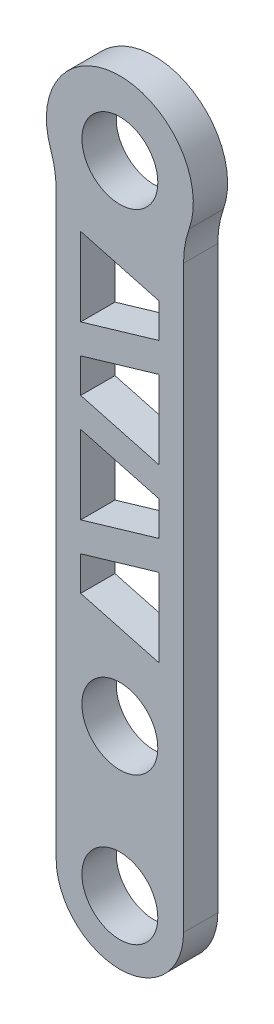
SolidWorks part; units mm, degrees
ref_plane "Front Plane" through (0, 0, 0) normal (0, 0, 1) x (1, 0, 0)
ref_plane "Top Plane" through (0, 0, 0) normal (0, 1, 0) x (1, 0, 0)
ref_plane "Right Plane" through (0, 0, 0) normal (1, 0, 0) x (0, 0, -1)
sketch "Sketch1" plane through (0, 0, 0) normal (0, 0, 1) x (1, 0, 0)
  line L0 (-1.1218, 98.318) -> (-1.1218, -78.4144) construction
  line L1 (-14.1218, 65.8174) -> (-14.1218, -52.5207)
  line L2 (-9.1218, 3.9577) -> (-9.1218, -3.0423)
  line L3 (-9.1218, -3.0423) -> (6.8782, -7.3295)
  line L4 (6.8782, -7.3295) -> (6.8782, 8.6705)
  line L5 (6.8782, 8.6705) -> (-9.1218, 3.9577)
  line L6 (-9.1218, 31.9577) -> (6.8782, 27.6705)
  line L7 (-9.1218, 38.9577) -> (-9.1218, 31.9577)
  line L8 (6.8782, 43.6705) -> (-9.1218, 38.9577)
  line L9 (6.8782, 27.6705) -> (6.8782, 43.6705)
  line L10 (6.8782, 56.6705) -> (-9.1218, 60.9577)
  line L11 (6.8782, 49.6705) -> (6.8782, 56.6705)
  line L12 (-9.1218, 44.9577) -> (6.8782, 49.6705)
  line L13 (-9.1218, 60.9577) -> (-9.1218, 44.9577)
  line L14 (-9.1218, 9.9577) -> (6.8782, 14.6705)
  line L15 (6.8782, 14.6705) -> (6.8782, 21.6705)
  line L16 (6.8782, 21.6705) -> (-9.1218, 25.9577)
  line L17 (-9.1218, 25.9577) -> (-9.1218, 9.9577)
  line L18 (11.8782, 65.8174) -> (11.8782, -52.5207)
  circle A0 centre (-1.1218, -52.5207) radius 7.75
  circle A1 centre (-1.1218, -22.5207) radius 7.75
  circle A2 centre (-1.1218, 77.4793) radius 7.75
  arc A3 (13.0211, 72.4813) -> (-15.2646, 72.4813) centre (-1.1218, 77.4793) ccw
  arc A4 (-14.1218, -52.5207) -> (11.8782, -52.5207) centre (-1.1218, -52.5207) ccw
  arc A5 (11.8782, 65.8174) -> (13.0211, 72.4813) centre (31.8782, 65.8174) cw
  arc A6 (-15.2646, 72.4813) -> (-14.1218, 65.8174) centre (-34.1218, 65.8174) cw
  point P29 (11.8782, 69.996)
  point P33 (-14.1218, 69.996)
  dimension "D1" = 15.5
  dimension "D15" = 30
  dimension "D16" = 20
  dimension "D17" = 20
  dimension "D2" = 30
  dimension "D3" = 100
  dimension "D4" = 13
  dimension "D5" = 5
  dimension "D6" = 7
  dimension "D7" = 16
  dimension "D8" = 75
  dimension "D9" = 16
  dimension "D10" = 2
  dimension "D11" = 6
  dimension "D13" = 6
  dimension "D14" = 6
  dimension "D12" = 2
extrude "Boss-Extrude1" add sketch "Sketch1" along normal blind 7
sketch "Sketch2" plane through (0, 0, 7) normal (0, 0, 1) x (1, 0, 0)
  circle A2 centre (-1.1218, 77.4793) radius 3.25
  circle A3 centre (-1.1218, 77.4793) radius 15
  dimension "D1" = 6.5
extrude "Boss-Extrude2" [suppressed] add sketch "Sketch2" along normal blind 51
